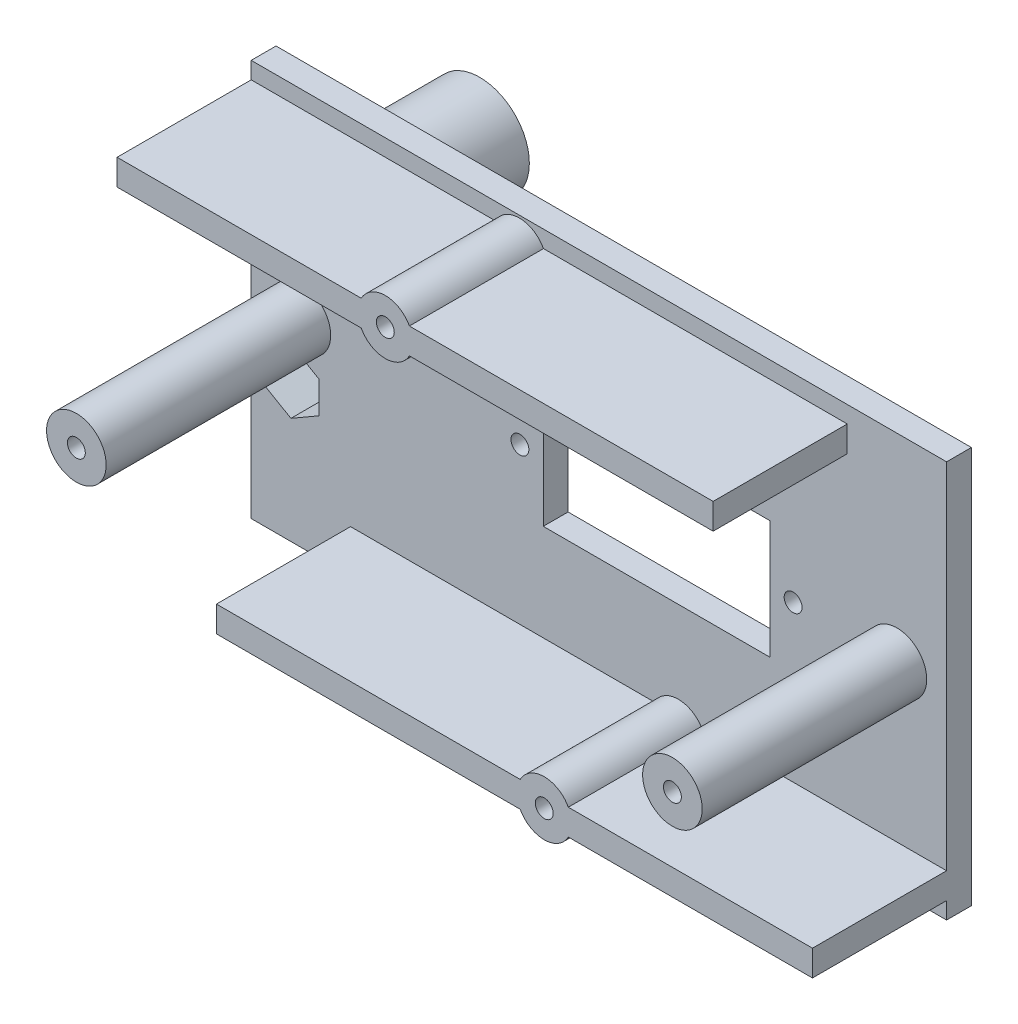
SolidWorks part; units mm, degrees
ref_plane "Front Plane" through (0, 0, 0) normal (0, 0, 1) x (1, 0, 0)
ref_plane "Top Plane" through (0, 0, 0) normal (0, 1, 0) x (1, 0, 0)
ref_plane "Right Plane" through (0, 0, 0) normal (1, 0, 0) x (0, 0, -1)
sketch "Sketch1" plane through (0, 0, 0) normal (0, 0, 1) x (1, 0, 0)
  line L0 (-35, -19.975) -> (35, -19.975)
  line L1 (35, -19.975) -> (35, 19.975)
  line L2 (35, 19.975) -> (-35, 19.975)
  line L3 (-35, 19.975) -> (-35, -19.975)
extrude "Boss-Extrude1" add sketch "Sketch1" along normal blind 2.5 from offset 2.5
sketch "Sketch2" plane through (0, 0, 0) normal (0, 0, 1) x (1, 0, 0)
  line L0 (-35, 15.675) -> (25, 15.675)
  line L1 (25, 15.675) -> (25, 18.275)
  line L2 (25, 18.275) -> (-35, 18.275)
  line L3 (-35, 18.275) -> (-35, 15.675)
extrude "Boss-Extrude2" add sketch "Sketch2" along normal blind 13.5
sketch "Sketch3" plane through (0, 0, 0) normal (0, 0, 1) x (1, 0, 0)
  line L0 (-25, -18.275) -> (35, -18.275)
  line L1 (35, -18.275) -> (35, -15.675)
  line L2 (35, -15.675) -> (-25, -15.675)
  line L3 (-25, -15.675) -> (-25, -18.275)
extrude "Boss-Extrude3" add sketch "Sketch3" along normal blind 13.5
sketch "Sketch4" plane through (0, 0, 0) normal (0, 0, 1) x (1, 0, 0)
  circle A0 centre (-8, 16.975) radius 2.75
  circle A1 centre (8, -16.975) radius 2.75
extrude "Boss-Extrude4" add sketch "Sketch4" along normal blind 13.5
sketch "Sketch5" plane through (0, 0, 0) normal (0, 0, 1) x (1, 0, 0)
  circle A0 centre (-31, 6) radius 5
  circle A1 centre (-31, -6) radius 5
extrude "Boss-Extrude5" add sketch "Sketch5" along normal blind 16.5 from offset 19
sketch "Sketch6" plane through (0, 0, 0) normal (0, 0, 1) x (1, 0, 0)
  circle A0 centre (30, 0) radius 3
  circle A1 centre (-30, 0) radius 3
extrude "Boss-Extrude6" add sketch "Sketch6" along normal blind 22.6
sketch "Sketch7" plane through (0, 0, 0) normal (0, 0, 1) x (1, 0, 0)
  circle A0 centre (30, 0) radius 0.9
  circle A1 centre (-30, 0) radius 0.9
extrude "Cut-Extrude1" cut sketch "Sketch7" along normal blind 8.1 from offset 14.6
sketch "Sketch8" plane through (0, 0, 0) normal (0, 0, 1) x (1, 0, 0)
  line L0 (-5.6, -5.95) -> (17.2, -5.95)
  line L1 (17.2, -5.95) -> (17.2, 5.95)
  line L2 (17.2, 5.95) -> (-5.6, 5.95)
  line L3 (-5.6, 5.95) -> (-5.6, -5.95)
extrude "Cut-Extrude2" cut sketch "Sketch8" against normal through all and the other way through all
sketch "Sketch9" plane through (0, 0, 0) normal (0, 0, 1) x (1, 0, 0)
  circle A0 centre (-7.95, 0) radius 0.9
  circle A1 centre (19.55, 0) radius 0.9
extrude "Cut-Extrude3" cut sketch "Sketch9" against normal through all and the other way through all
sketch "Sketch10" plane through (0, 0, 0) normal (0, 0, 1) x (1, 0, 0)
  circle A0 centre (-8, 16.975) radius 0.9
  circle A1 centre (8, -16.975) radius 0.9
extrude "Cut-Extrude4" cut sketch "Sketch10" against normal through all and the other way through all
sketch "Sketch11" plane through (0, 0, 0) normal (0, 0, 1) x (1, 0, 0)
  circle A0 centre (-31, 6) radius 1.725
  circle A1 centre (-31, -6) radius 1.725
extrude "Cut-Extrude5" cut sketch "Sketch11" against normal through all and the other way through all
sketch "Sketch12" plane through (0, 0, 0) normal (0, 0, 1) x (1, 0, 0)
  line L0 (-28.2, 7.6166) -> (-31, 9.2332)
  line L1 (-31, 9.2332) -> (-33.8, 7.6166)
  line L2 (-33.8, 7.6166) -> (-33.8, 4.3834)
  line L3 (-33.8, 4.3834) -> (-31, 2.7668)
  line L4 (-31, 2.7668) -> (-28.2, 4.3834)
  line L5 (-28.2, 4.3834) -> (-28.2, 7.6166)
  line L6 (-28.2, -4.3834) -> (-31, -2.7668)
  line L7 (-31, -2.7668) -> (-33.8, -4.3834)
  line L8 (-33.8, -4.3834) -> (-33.8, -7.6166)
  line L9 (-33.8, -7.6166) -> (-31, -9.2332)
  line L10 (-31, -9.2332) -> (-28.2, -7.6166)
  line L11 (-28.2, -7.6166) -> (-28.2, -4.3834)
extrude "Cut-Extrude6" cut sketch "Sketch12" along normal blind 4.2 from offset 4.2
